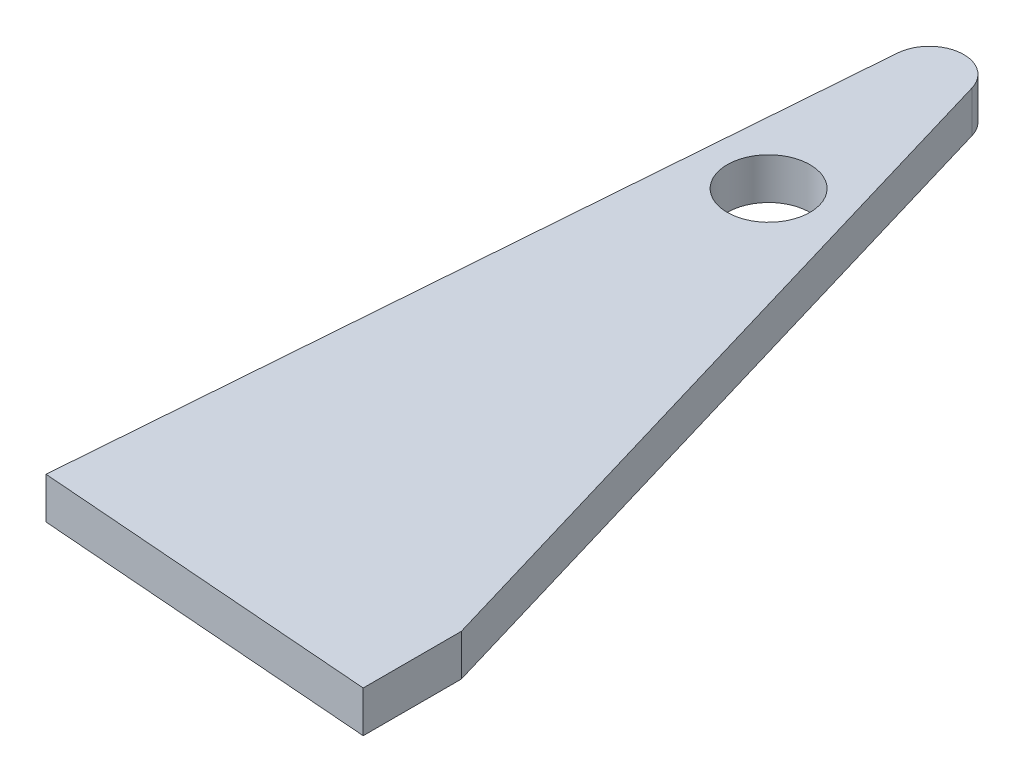
SolidWorks part; units mm, degrees
ref_plane "Front Plane" through (0, 0, 0) normal (0, 0, 1) x (1, 0, 0)
ref_plane "Top Plane" through (0, 0, 0) normal (0, 1, 0) x (1, 0, 0)
ref_plane "Right Plane" through (0, 0, 0) normal (1, 0, 0) x (0, 0, -1)
sketch "Sketch1" plane through (0, 0, 0) normal (0, 1, 0) x (1, 0, 0)
  line L0 (0, 0) -> (8.8452, 114.6593)
  line L1 (18.6241, 115.6962) -> (49.8519, 10.3823)
  line L2 (49.8519, -3.8457) -> (0, 0)
  line L3 (49.8519, 10.3823) -> (49.8519, -3.8457)
  arc A0 (18.6241, 115.6962) -> (8.8452, 114.6593) centre (13.8304, 114.2748) ccw
  circle A1 centre (16.5156, 88.2891) radius 6
  point P4 (18.6241, 88.4974)
  point P6 (10.9275, 141.6524)
  point P9 (0, 0)
  point P12 (16.0699, 89.2573)
  point P13 (16.5156, 88.2891)
  dimension "D3" = 5
  dimension "D4" = 12
  dimension "D1" = 50
  dimension "D2" = 115
extrude "Boss-Extrude1" add sketch "Sketch1" along normal blind 6 contours L1 L2 L0 A0
